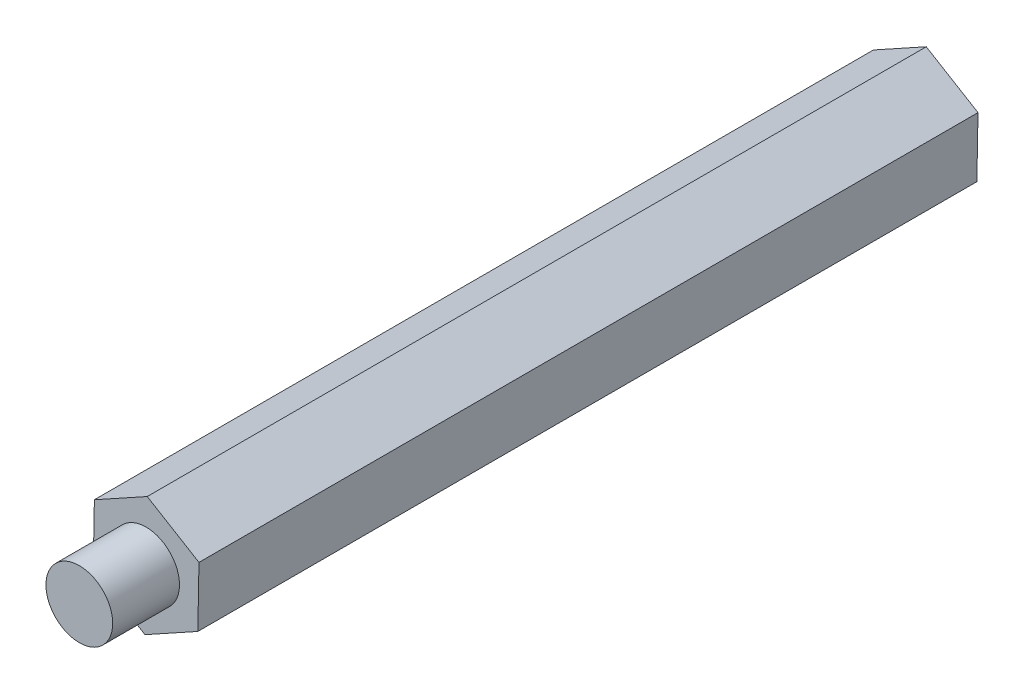
SolidWorks part; units mm, degrees
ref_plane "前视基准面" through (0, 0, 0) normal (0, 0, 1) x (1, 0, 0)
ref_plane "上视基准面" through (0, 0, 0) normal (0, 1, 0) x (1, 0, 0)
ref_plane "右视基准面" through (0, 0, 0) normal (1, 0, 0) x (0, 0, -1)
other "Configuration Table"
sketch "草图1" plane through (0, 0, 0) normal (0, 0, 1) x (1, 0, 0)
  line L1 (-2.3242, 1.4005) -> (-2.375, -1.3126)
  line L2 (-2.375, -1.3126) -> (-0.0508, -2.7131)
  line L3 (-0.0508, -2.7131) -> (2.3242, -1.4005)
  line L4 (2.3242, -1.4005) -> (2.375, 1.3126)
  line L5 (2.375, 1.3126) -> (0.0508, 2.7131)
  line L6 (0.0508, 2.7131) -> (-2.3242, 1.4005)
  circle A0 centre (0, 0) radius 2.35 construction
  point P1 (-1.1367, 2.0568)
  point P10 (1.1367, -2.0568)
  dimension "D1" = 4.7
extrude "凸台-拉伸1" add sketch "草图1" along normal blind 35
sketch "草图2" plane through (0, 0, 35) normal (0, 0, 1) x (1, 0, 0)
  circle A0 centre (0, 0) radius 1.5
  dimension "D1" = 3
extrude "凸台-拉伸2" add sketch "草图2" along normal blind 3
sketch "草图3" plane through (0, 0, 0) normal (0, 0, -1) x (-1, 0, 0)
  circle A0 centre (0, 0) radius 1.5
  dimension "D1" = 3
extrude "切除-拉伸1" cut sketch "草图3" against normal blind 3
